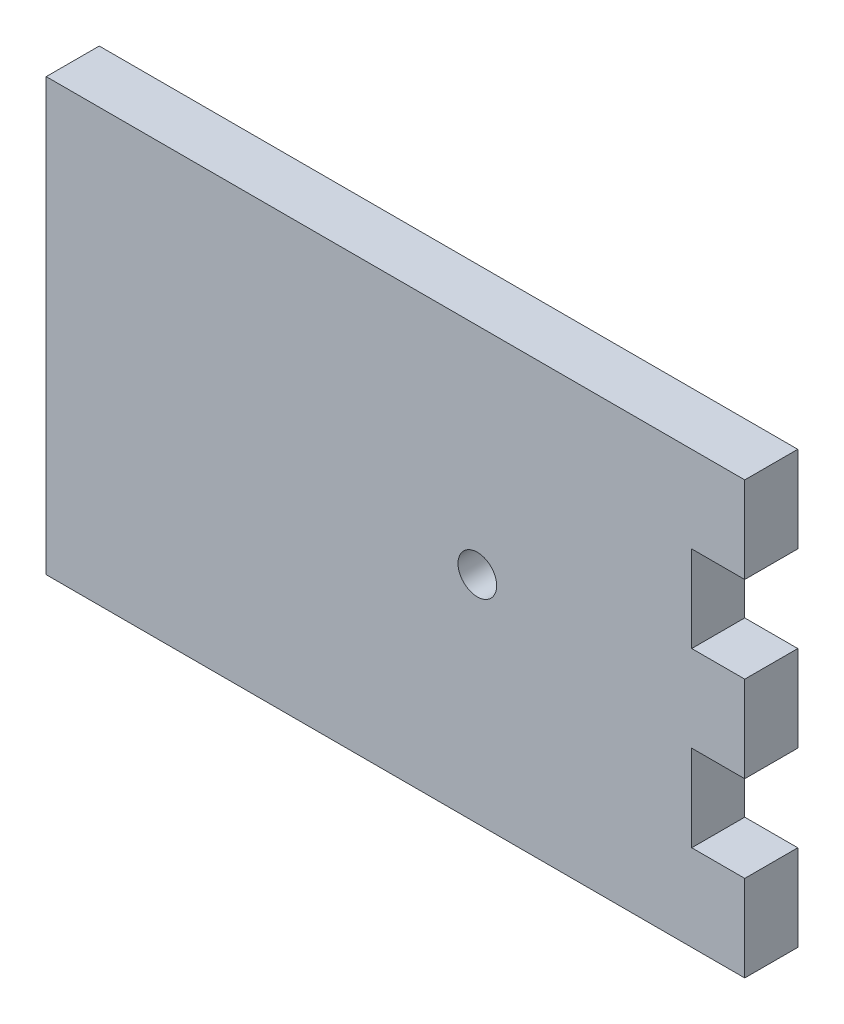
SolidWorks part; units mm, degrees
ref_plane "Front Plane" through (0, 0, 0) normal (0, 0, 1) x (1, 0, 0)
ref_plane "Top Plane" through (0, 0, 0) normal (0, 1, 0) x (1, 0, 0)
ref_plane "Right Plane" through (0, 0, 0) normal (1, 0, 0) x (0, 0, -1)
sketch "Sketch2" plane through (0, 0, 0) normal (0, 0, 1) x (1, 0, 0)
  line L1 (0, 0) -> (63.246, 0)
  line L2 (0, 0) -> (0, 39.0586)
  line L3 (0, 39.0586) -> (63.246, 39.0586)
  line L4 (63.246, 0) -> (63.246, 39.0586)
  line L5 (0, 0) -> (63.246, 39.0586) construction
  line L6 (0, 39.0586) -> (63.246, 0) construction
  point P4 (31.623, 19.5293)
  dimension "D1" = 39.0586
  dimension "D2" = 63.246
extrude "Boss-Extrude1" add sketch "Sketch2" along normal blind 4.8
sketch "Sketch5" plane through (0, 0, 4.8) normal (0, 0, 1) x (1, 0, 0)
  line L0 (63.246, 0) -> (63.246, 39.0586) construction
  line L1 (63.246, 7.8117) -> (58.446, 7.8117)
  line L2 (63.246, 7.8117) -> (63.246, 15.6234)
  line L3 (63.246, 15.6234) -> (58.446, 15.6234)
  line L4 (58.446, 7.8117) -> (58.446, 15.6234)
  line L5 (63.246, 7.8117) -> (58.446, 15.6234) construction
  line L6 (63.246, 15.6234) -> (58.446, 7.8117) construction
  line L7 (63.246, 0) -> (63.246, 7.8117) construction
  line L8 (63.246, 23.4352) -> (58.446, 23.4352)
  line L9 (63.246, 23.4352) -> (63.246, 31.2469)
  line L10 (63.246, 31.2469) -> (58.446, 31.2469)
  line L11 (58.446, 23.4352) -> (58.446, 31.2469)
  line L12 (63.246, 23.4352) -> (58.446, 31.2469) construction
  line L13 (63.246, 31.2469) -> (58.446, 23.4352) construction
  line L14 (63.246, 15.6234) -> (63.246, 23.4352) construction
  line L15 (63.246, 31.2469) -> (63.246, 39.0586) construction
  line L16 (63.246, 15.6234) -> (63.246, 23.4352)
  line L17 (63.246, 31.2469) -> (63.246, 39.0586) construction
  point P4 (60.846, 11.7176)
  point P11 (60.846, 27.341)
  line M6 (63.246, 0) -> (63.246, 39.0586)
  dimension "D1" = 7.8117
  dimension "D2" = 4.8
extrude "Cut-Extrude1" cut sketch "Sketch5" against normal through all contours L4 L1 L3 M6 | L11 L8 L10 M6
ref_plane "Plane1" through (0, 19.5293, 0) normal (0, 1, 0) x (1, 0, 0)
sketch "Sketch6" plane through (0, 0, 4.8) normal (0, 0, 1) x (1, 0, 0)
  circle A1 centre (39.0321, 19.5293) radius 1.75
extrude "Cut-Extrude2" cut sketch "Sketch6" against normal through all
equation "\"MDF\"= 4.8mm"
equation "\"Foamcore\"= 4.6mm"
equation "\"PCB\"= 1.6mm"
equation "\"GMaterial\"= \"MDF\""
equation "\"BaseWidth\"= 10in"
equation "\"SkidLength\"= 1in"
equation "\"SkidClearance\"= 0.4in"
equation "\"MotorMountLength\"= 2in"
equation "\"MotorMountWidth\"= \"GMaterial\""
equation "\"MotorMountHeight\"= 2in"
equation "\"UnoStackWidth\"= 77.4mm"
equation "\"UnoStackLength\"= 79.8mm"
equation "\"UnoStackHeight\"= 34.2mm"
equation "\"TallHexRiserHeight\"= 22.2mm"
equation "\"PingPongBallSize\"= 40mm"
equation "\"BarrelLength\"= 9in"
equation "\"BarrelSize\"= \"PingPongBallSize\""
equation "\"PlatformLength\"= 4in"
equation "\"PlatformWidth\"= 5in"
equation "\"WheelWidth\"= 26mm"
equation "\"WheelDiameter\"= 63mm"
equation "\"ServoMountLength\"=1.53774"
equation "\"ServoMountHeight\"=2.49223"
equation "\"D1@Sketch5\"=\"ServoMountLength\"/5"
equation "\"D2@Sketch5\"=\"GMaterial\""
equation "\"ServoGearHeight\"= 0.95907867in"
equation "\"PivotHoleRadius\"=0.616358"
